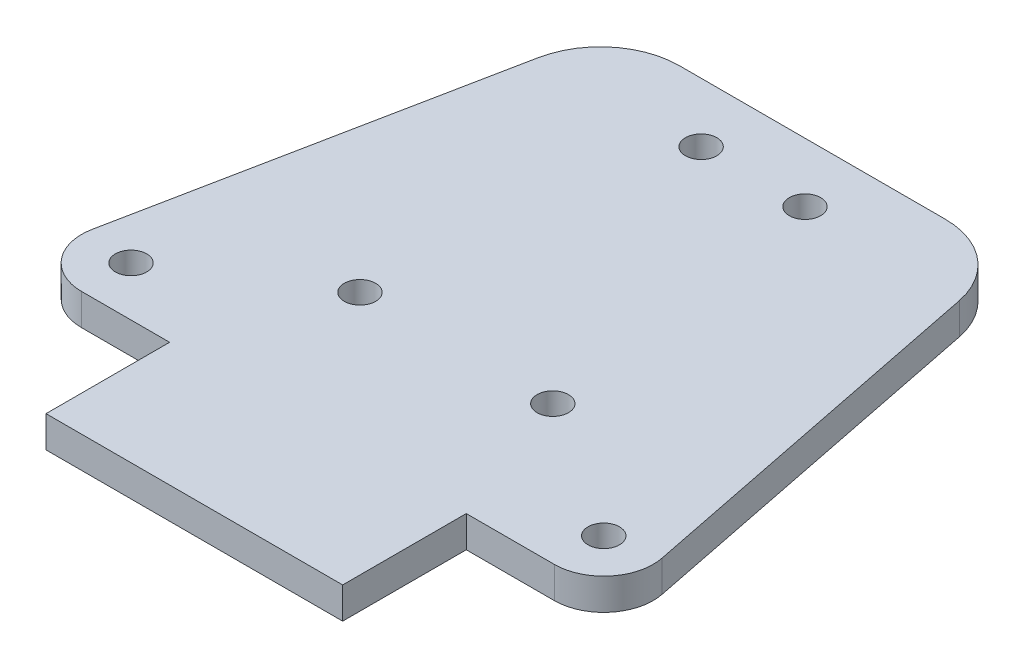
SolidWorks part; units mm, degrees
ref_plane "Alzado" through (0, 0, 0) normal (0, 0, 1) x (1, 0, 0)
ref_plane "Planta" through (0, 0, 0) normal (0, 1, 0) x (1, 0, 0)
ref_plane "Vista lateral" through (0, 0, 0) normal (1, 0, 0) x (0, 0, -1)
sketch "Croquis1" plane through (0, 0, 0) normal (0, 1, 0) x (1, 0, 0)
  line L0 (8.7138, 43.5689) -> (0, 0)
  line L1 (16.5584, 50) -> (43.4416, 50)
  line L3 (0, 0) -> (60, 0)
  line L5 (51.2862, 43.5689) -> (60, 0)
  line L11 (30, -1000) -> (30, 49000) construction
  circle A0 centre (20.25, 14) radius 9.5 construction
  circle A1 centre (39.75, 14) radius 9.5 construction
  circle A2 centre (20.25, 14) radius 12.5 construction
  circle A3 centre (39.75, 14) radius 12.5 construction
  circle A4 centre (39.75, 14) radius 1.5875
  circle A6 centre (20.25, 14) radius 1.5875
  circle A7 centre (24.75, 44) radius 1.5875
  circle A8 centre (35.25, 44) radius 1.5875
  circle A9 centre (24.75, 44) radius 4.7625 construction
  circle A10 centre (35.25, 44) radius 4.7625 construction
  arc A11 (51.2862, 43.5689) -> (43.4416, 50) centre (43.4416, 42) ccw
  arc A12 (8.7138, 43.5689) -> (16.5584, 50) centre (16.5584, 42) cw
  point P7 (50, 50)
  point P15 (30, 0)
  point P38 (10, 50)
  dimension "D6" = 19
  dimension "D7" = 19
  dimension "D5" = 25
  dimension "D10" = 25
  dimension "D20" = 3.175
  dimension "D21" = 3.175
  dimension "D22" = 3.175
  dimension "D26" = 9.525
  dimension "D27" = 9.525
  dimension "D29" = 8
  dimension "D12" = 3.175
  dimension "D1" = 60
  dimension "D3" = 40
  dimension "D4" = 20
  dimension "D8" = 19.5
  dimension "D9" = 14
  dimension "D11" = 9.75
  dimension "D23" = 4.5
  dimension "D24" = 4.5
  dimension "D25" = 30
  dimension "D28" = 50
extrude "Saliente-Extruir1" add sketch "Croquis1" along normal blind 3.175
sketch "Croquis2" plane through (0, 3.175, 0) normal (0, 1, 0) x (1, 0, 0)
  line L0 (0, 0) -> (60, 0) construction
  line L2 (60, 0) -> (51.2862, 43.5689) construction
  line L3 (53.901, 0) -> (60, 0)
  line L7 (43.4416, 50) -> (16.5584, 50)
  line L8 (8.7138, 43.5689) -> (0, 0)
  line L9 (0, 0) -> (60, 0)
  line L10 (60, 0) -> (51.2862, 43.5689)
  line L12 (1.1961, 5.9806) -> (0, 0)
  line L13 (0, 0) -> (6.099, 0)
  line L14 (60, 0) -> (58.8039, 5.9806)
  circle A1 centre (6.099, 5) radius 1.5875
  circle A2 centre (53.901, 5) radius 1.5875
  circle A3 centre (24.75, 44) radius 4.7625 construction
  circle A4 centre (35.25, 44) radius 4.7625 construction
  arc A6 (53.901, 0) -> (58.8039, 5.9806) centre (53.901, 5) ccw
  arc A7 (1.1961, 5.9806) -> (6.099, 0) centre (6.099, 5) ccw
  arc A9 (51.2862, 43.5689) -> (43.4416, 50) centre (43.4416, 42) ccw
  arc A10 (16.5584, 50) -> (8.7138, 43.5689) centre (16.5584, 42) ccw
  dimension "D1" = 9.525
  dimension "D2" = 9.525
  dimension "D4" = 3.175
  dimension "D5" = 3.175
  dimension "D6" = 5
  dimension "D7" = 10
  dimension "D9" = 5
  dimension "D8" = 0
extrude "Cortar-Extruir1" cut sketch "Croquis2" against normal blind 3.175
sketch "Croquis3" plane through (0, 3.175, 0) normal (0, 1, 0) x (1, 0, 0)
  line L0 (30, -1000) -> (30, 49000) construction
  line L1 (6.099, 0) -> (53.901, 0) construction
  line L2 (15, 0) -> (45, 0)
  line L3 (45, -12.5) -> (15, -12.5)
  line L4 (15, 0) -> (15, -12.5)
  line L10 (45, 0) -> (45, -12.5)
  point P5 (30, 0)
  point P6 (30, 0)
  dimension "D1" = 30
  dimension "D5" = 12.5
extrude "Saliente-Extruir2" add sketch "Croquis3" against normal blind 3.175
